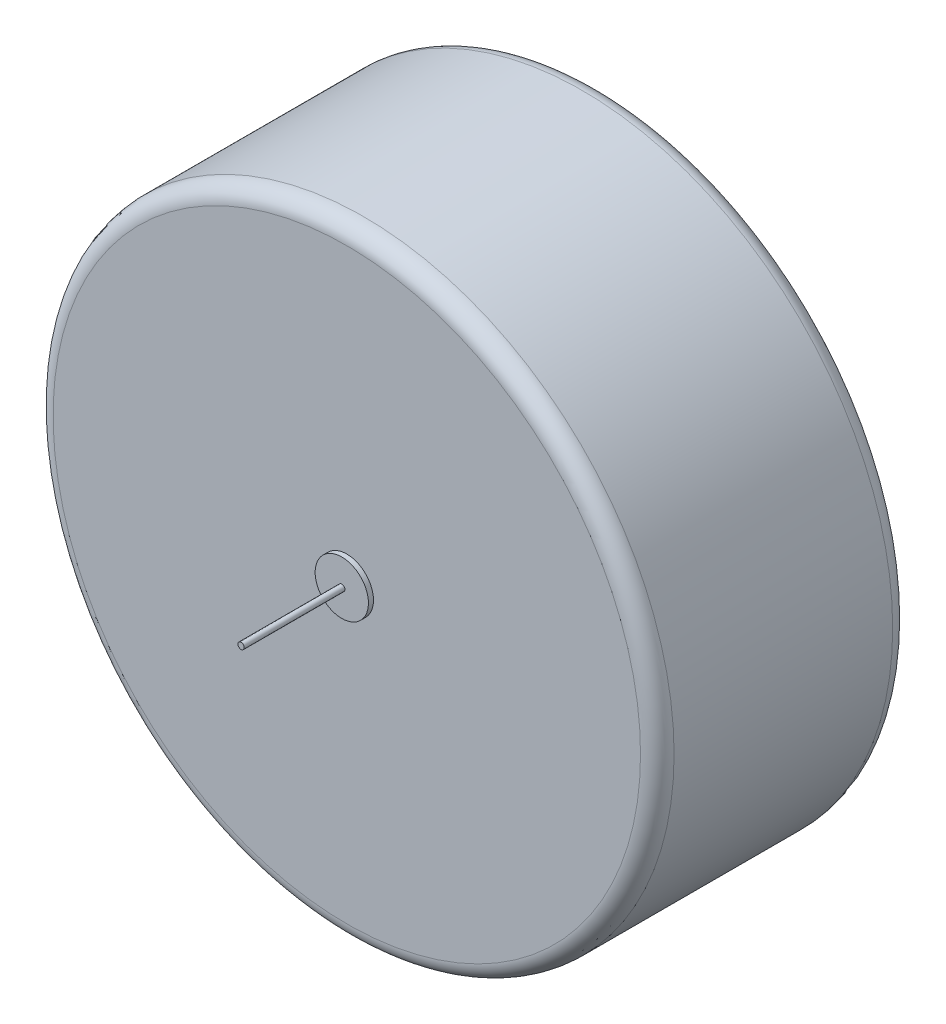
SolidWorks part; units mm, degrees
ref_plane "Front Plane" through (0, 0, 0) normal (0, 0, 1) x (1, 0, 0)
ref_plane "Top Plane" through (0, 0, 0) normal (0, 1, 0) x (1, 0, 0)
ref_plane "Right Plane" through (0, 0, 0) normal (1, 0, 0) x (0, 0, -1)
sketch "Sketch1" plane through (0, 0, 0) normal (0, 0, 1) x (1, 0, 0)
  circle A0 centre (0, 0) radius 37
  dimension "D1" = 74
extrude "Boss-Extrude1" add sketch "Sketch1" against normal blind 30.05
sketch "Sketch2" plane through (0, 0, 0) normal (0, 0, 1) x (1, 0, 0)
  circle A0 centre (0, 0) radius 3.175
  dimension "D1" = 6.35
extrude "Boss-Extrude2" add sketch "Sketch2" along normal blind 0.6
sketch "Sketch3" plane through (0, 0, 0.6) normal (0, 0, 1) x (1, 0, 0)
  circle A0 centre (0, 0) radius 0.375
  dimension "D1" = 0.75
extrude "Boss-Extrude3" add sketch "Sketch3" along normal blind 12
fillet "Fillet1" radius 2 2 edges at (37, 0, -30.05) (37, 0, 0)
